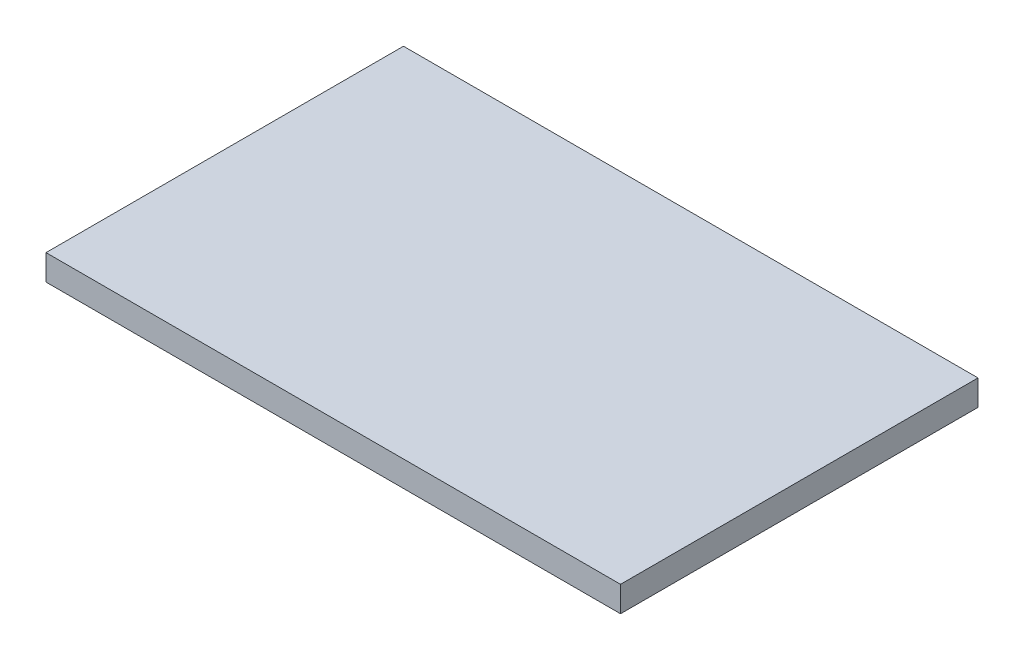
SolidWorks part; units mm, degrees
ref_plane "Front Plane" through (0, 0, 0) normal (0, 0, 1) x (1, 0, 0)
ref_plane "Top Plane" through (0, 0, 0) normal (0, 1, 0) x (1, 0, 0)
ref_plane "Right Plane" through (0, 0, 0) normal (1, 0, 0) x (0, 0, -1)
sketch "Sketch1" plane through (0, 0, 0) normal (0, 1, 0) x (1, 0, 0)
  line L1 (-562.5, 350) -> (562.5, 350)
  line L2 (-562.5, 350) -> (-562.5, -350)
  line L3 (-562.5, -350) -> (562.5, -350)
  line L4 (562.5, 350) -> (562.5, -350)
  line L5 (-562.5, 350) -> (562.5, -350) construction
  line L6 (-562.5, -350) -> (562.5, 350) construction
  point P0 (0, 0)
  point P5 (-562.5, 0)
  point P6 (562.5, 0)
  dimension "D1" = 700
  dimension "D2" = 1125
extrude "Boss-Extrude1" add sketch "Sketch1" along normal mid plane 50
sketch "Sketch2" plane through (562.5, 0, 0) normal (1, 0, 0) x (0, 0, -1)
  line L0 (-350, 0) -> (350, 0)
  line L1 (-350, 25) -> (-350, -25) construction
  line L2 (350, 25) -> (350, -25) construction
sketch "Sketch3" plane through (-562.5, 0, 0) normal (-1, 0, 0) x (0, 0, 1)
  line L0 (-350, 0) -> (350, 0)
  line L1 (-350, 25) -> (-350, -25) construction
  line L2 (350, 25) -> (350, -25) construction
